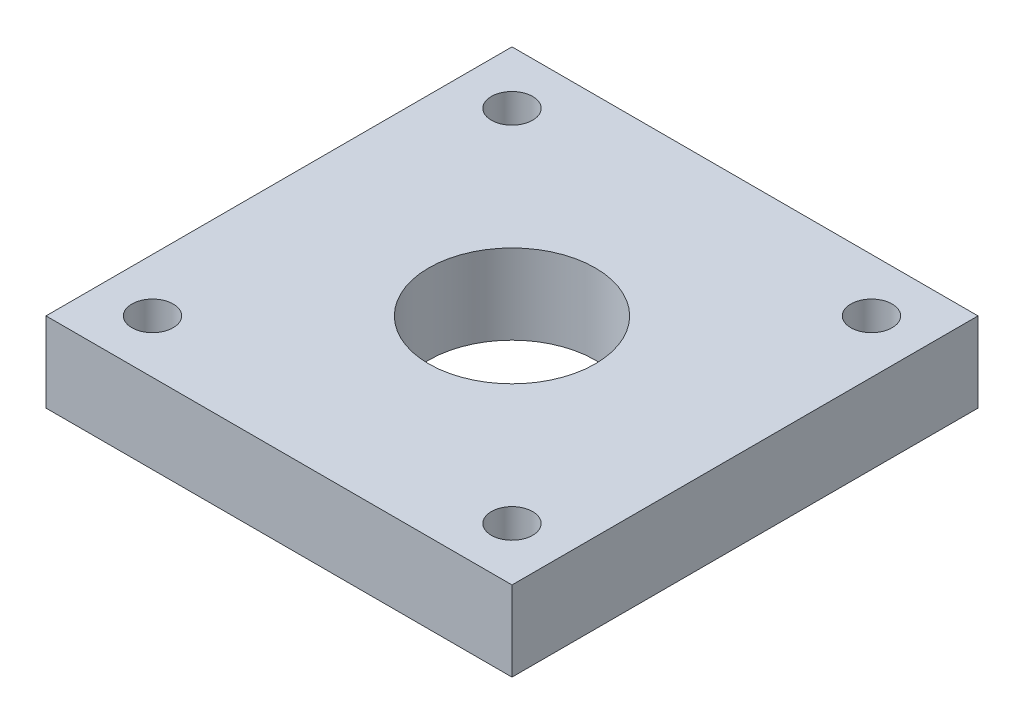
SolidWorks part; units mm, degrees
ref_plane "Front Plane" through (0, 0, 0) normal (0, 0, 1) x (1, 0, 0)
ref_plane "Top Plane" through (0, 0, 0) normal (0, 1, 0) x (1, 0, 0)
ref_plane "Right Plane" through (0, 0, 0) normal (1, 0, 0) x (0, 0, -1)
sketch "Sketch1" plane through (0, 0, 0) normal (0, 1, 0) x (1, 0, 0)
  line L0 (0, 5.7902) -> (0, 0) construction
  line L1 (-17.5, -17.5) -> (17.5, -17.5)
  line L2 (-17.5, -17.5) -> (-17.5, 17.5)
  line L3 (-17.5, 17.5) -> (17.5, 17.5)
  line L4 (17.5, -17.5) -> (17.5, 17.5)
  line L5 (-17.5, -17.5) -> (17.5, 17.5) construction
  line L6 (-17.5, 17.5) -> (17.5, -17.5) construction
  line L7 (0, 0) -> (5.2429, 0) construction
  circle A1 centre (0, 0) radius 6.25
  point P0 (0, 0)
  dimension "D5" = 12.5
  dimension "D1" = 35
  dimension "D2" = 35
extrude "Boss-Extrude1" add sketch "Sketch1" along normal blind 6
hole_wizard "M3 Clearance Hole1" positions "Sketch2" profile "Sketch3" hole size "M3" standard "ISO" end condition through all
sketch "Sketch2" plane through (0, 6, 0) normal (0, 1, 0) x (1, 0, 0)
  line L1 (13.5, -13.5) -> (-13.5, -13.5)
  line L2 (13.5, -13.5) -> (13.5, 13.5)
  line L3 (13.5, 13.5) -> (-13.5, 13.5)
  line L4 (-13.5, -13.5) -> (-13.5, 13.5)
  line L5 (13.5, -13.5) -> (-13.5, 13.5) construction
  line L6 (13.5, 13.5) -> (-13.5, -13.5) construction
  line L7 (-17.5, 17.5) -> (-17.5, -17.5) construction
  line L8 (17.5, 17.5) -> (-17.5, 17.5) construction
  point P0 (-13.5, 13.5)
  point P2 (13.5, 13.5)
  point P4 (13.5, -13.5)
  point P6 (-13.5, -13.5)
  point P9 (0, 0)
  point P76 (0, 0)
  point P77 (0, 0)
  point P78 (0, 0)
  point P79 (0, 0)
  dimension "D1" = 4
  dimension "D2" = 4
sketch "Sketch3" plane through (-13.5, 6, -13.5) normal (1, 0, 0) x (0, 0, 1)
  line L0 (0, 0) -> (0, 6)
  line L1 (0, 6) -> (1.55, 6)
  line L2 (1.55, 6) -> (1.55, 0)
  line L5 (1.55, 0) -> (0, 0)
  line L11 (0, -6.35) -> (0, 107.95) construction
  dimension "Thru Hole Dia." = 3.1
  dimension "Thru Hole Depth" = 6
